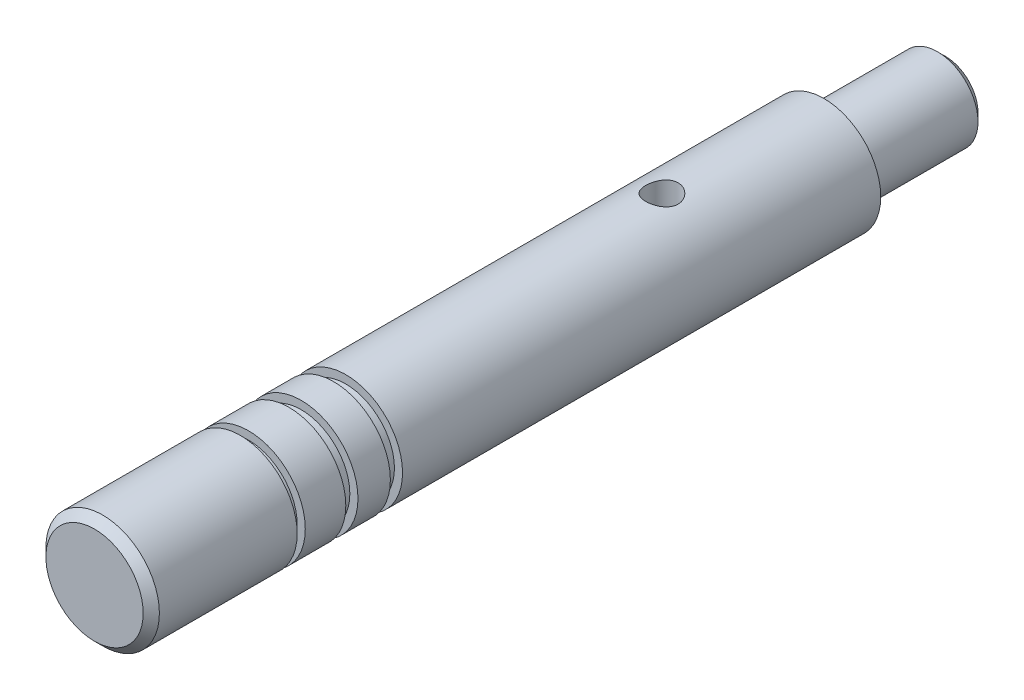
SolidWorks part; units mm, degrees
material "Alliage de zinc AC41A, brut"
ref_plane "Plan de face" through (0, 0, 0) normal (0, 0, 1) x (1, 0, 0)
ref_plane "Plan de dessus" through (0, 0, 0) normal (0, 1, 0) x (1, 0, 0)
ref_plane "Plan de droite" through (0, 0, 0) normal (1, 0, 0) x (0, 0, -1)
sketch "Esquisse1" plane through (0, 0, 0) normal (0, 0, 1) x (1, 0, 0)
  circle A0 centre (0, 0) radius 2.5
  dimension "D1" = 5
extrude "Boss.-Extru.1" add sketch "Esquisse1" along normal blind 7.5
sketch "Esquisse2" plane through (0, 0, 7.5) normal (0, 0, 1) x (1, 0, 0)
  circle A0 centre (0, 0) radius 3.5
  dimension "D1" = 7
extrude "Boss.-Extru.2" add sketch "Esquisse2" along normal blind 29.5
sketch "Esquisse3" plane through (0, 0, 37) normal (0, 0, 1) x (1, 0, 0)
  circle A0 centre (0, 0) radius 3
  dimension "D1" = 6
extrude "Boss.-Extru.3" add sketch "Esquisse3" along normal blind 0.75
sketch "Esquisse4" plane through (0, 0, 37.75) normal (0, 0, 1) x (1, 0, 0)
  circle A0 centre (0, 0) radius 3.5
  dimension "D1" = 7
extrude "Boss.-Extru.4" add sketch "Esquisse4" along normal blind 2
sketch "Esquisse5" plane through (0, 0, 39.75) normal (0, 0, 1) x (1, 0, 0)
  circle A0 centre (0, 0) radius 3
  dimension "D1" = 6
extrude "Boss.-Extru.5" add sketch "Esquisse5" along normal blind 0.75
sketch "Esquisse6" plane through (0, 0, 40.5) normal (0, 0, 1) x (1, 0, 0)
  circle A0 centre (0, 0) radius 3.5
  dimension "D1" = 7
extrude "Boss.-Extru.6" add sketch "Esquisse6" along normal blind 2.5
sketch "Esquisse7" plane through (0, 0, 43) normal (0, 0, 1) x (1, 0, 0)
  circle A0 centre (0, 0) radius 3
  dimension "D1" = 6
extrude "Boss.-Extru.7" add sketch "Esquisse7" along normal blind 0.5
sketch "Esquisse8" plane through (0, 0, 43.5) normal (0, 0, 1) x (1, 0, 0)
  circle A0 centre (0, 0) radius 3.5
  dimension "D1" = 7
extrude "Boss.-Extru.8" add sketch "Esquisse8" along normal blind 9
cosmetic thread "Représentation de filetage1" parameters "D2"=6
chamfer "Chanfrein2" distance 0.5 angle 45 2 edges at (2.5, 0, 0) (3.5, 0, 52.5)
sketch "Esquisse9" plane through (0, 0, 0) normal (0, 1, 0) x (1, 0, 0)
  line L0 (0, -7.5) -> (0, -17.5) construction
  line L1 (3.5, -7.5) -> (-3.5, -7.5) construction
  circle A0 centre (0, -17.5) radius 1
  dimension "D2" = 2
  dimension "D1" = 10
extrude "Enlèv. mat.-Extru.1" cut sketch "Esquisse9" against normal through all and the other way through all contours A0
